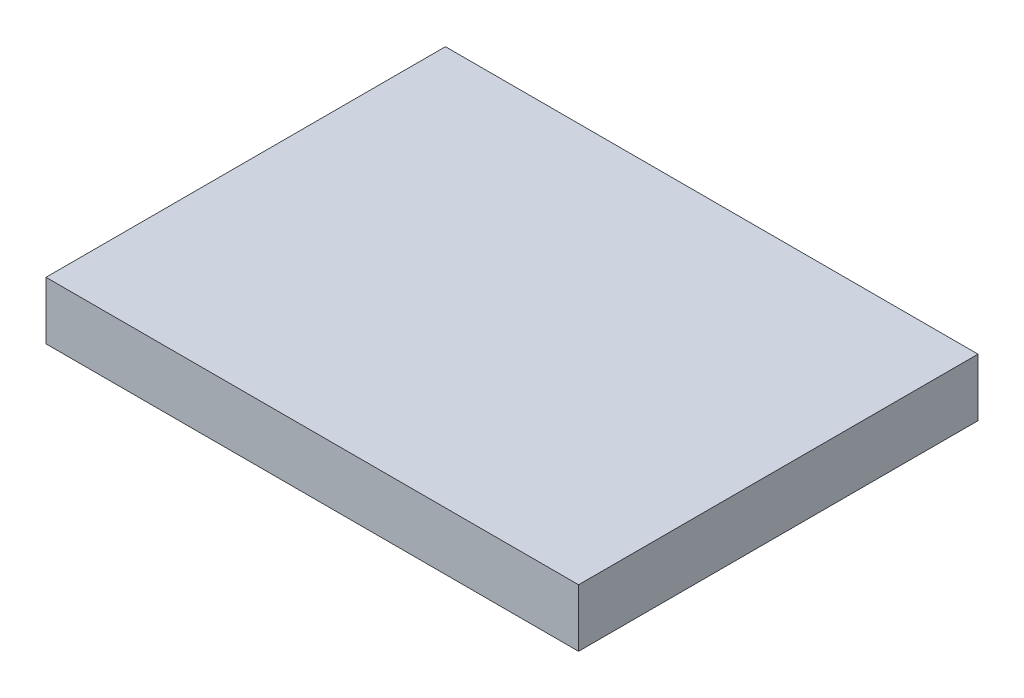
SolidWorks part; units mm, degrees
ref_plane "Front Plane" through (0, 0, 0) normal (0, 0, 1) x (1, 0, 0)
ref_plane "Top Plane" through (0, 0, 0) normal (0, 1, 0) x (1, 0, 0)
ref_plane "Right Plane" through (0, 0, 0) normal (1, 0, 0) x (0, 0, -1)
sketch "Sketch1" plane through (0, 0, 0) normal (0, 1, 0) x (1, 0, 0)
  line L1 (0, 0) -> (40.64, 0)
  line L2 (0, 0) -> (0, 30.48)
  line L3 (0, 30.48) -> (40.64, 30.48)
  line L4 (40.64, 0) -> (40.64, 30.48)
  dimension "D1" = 40.64
  dimension "D2" = 30.48
extrude "Boss-Extrude1" add sketch "Sketch1" along normal blind 4.4
